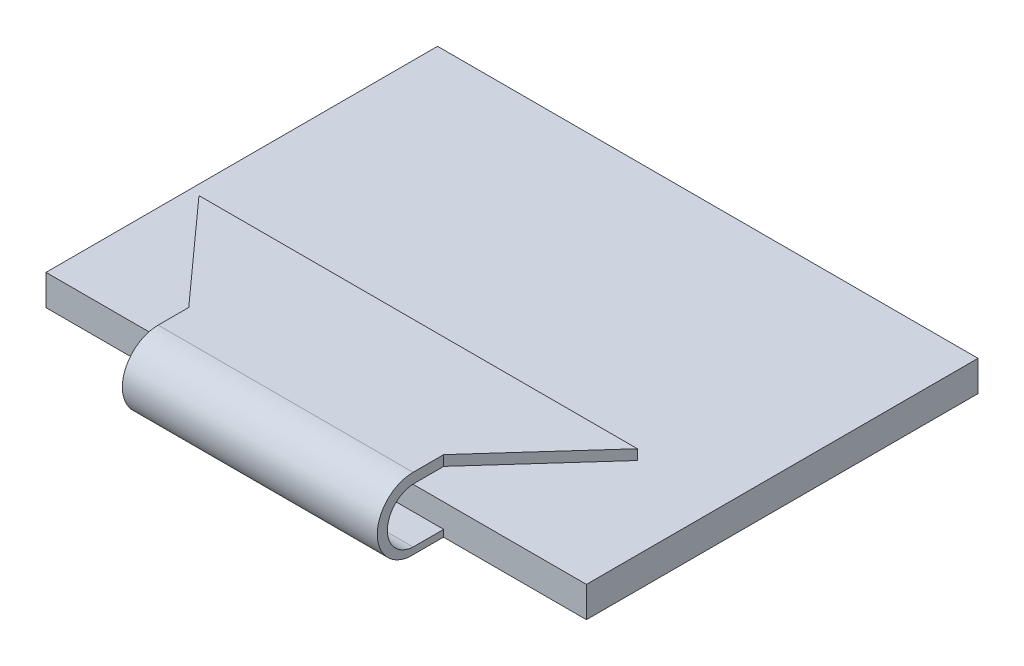
SolidWorks part; units mm, degrees
material "Glass"
ref_plane "Front Plane" through (0, 0, 0) normal (0, 0, 1) x (1, 0, 0)
ref_plane "Top Plane" through (0, 0, 0) normal (0, 1, 0) x (1, 0, 0)
ref_plane "Right Plane" through (0, 0, 0) normal (1, 0, 0) x (0, 0, -1)
sketch "Sketch1" plane through (0, 0, 0) normal (0, 1, 0) x (1, 0, 0)
  line L1 (-9.2826, 6.5217) -> (17.2174, 6.5217)
  line L2 (-9.2826, 6.5217) -> (-9.2826, -12.6783)
  line L3 (-9.2826, -12.6783) -> (17.2174, -12.6783)
  line L4 (17.2174, 6.5217) -> (17.2174, -12.6783)
  dimension "D1" = 19.2
  dimension "D2" = 26.5
extrude "Boss-Extrude1" add sketch "Sketch1" along normal blind 1.5
sketch "Sketch2" plane through (0, 0, 12.6783) normal (0, 0, 1) x (1, 0, 0)
  line L0 (-9.2826, 1.5) -> (-9.2826, 0) construction
  line L1 (-2.2826, 0.01) -> (10.2174, 0.01)
  line L2 (-2.2826, 0.01) -> (-2.2826, 3.51)
  line L3 (-2.2826, 3.51) -> (10.2174, 3.51)
  line L4 (10.2174, 0.01) -> (10.2174, 3.51)
  line L5 (-9.2826, 0) -> (17.2174, 0) construction
  dimension "D1" = 12.5
  dimension "D2" = 7
  dimension "D3" = 0.01
  dimension "D4" = 3.5
extrude "Boss-Extrude2" add sketch "Sketch2" along normal blind 3.5 contours L3 L4 L1 L2
sketch "Sketch3" plane through (-2.2826, 0, 0) normal (-1, 0, 0) x (0, 0, 1)
  line L0 (16.1783, 3.51) -> (12.6783, 3.51) construction
  line L1 (16.1783, 0.01) -> (16.1783, 3.51) construction
  line L2 (12.6783, 3.01) -> (12.6783, 0.3368)
  line L3 (14.1782, -0.0031) -> (12.6783, 0.01)
  line L4 (12.6783, 0.01) -> (12.6783, 1.5) construction
  line L5 (16.1783, 0.01) -> (12.6783, 0.01) construction
  line L6 (12.6783, 0.3368) -> (14.1783, 0.3368)
  line L7 (12.6783, 0.01) -> (12.6783, 0.3368)
  line L8 (14.1783, 3.51) -> (12.6783, 3.51)
  line L9 (12.6783, 1.5) -> (12.6783, 3.51) construction
  line L10 (12.6783, 3.51) -> (12.6783, 3.01)
  line L11 (12.6783, 3.01) -> (14.1783, 3.01)
  line L12 (14.1783, 3.51) -> (16.1783, 3.51)
  line L13 (16.1783, 3.51) -> (16.1783, 0.01)
  line L14 (16.1783, 0.01) -> (14.1782, -0.0031)
  arc A0 (14.1783, 3.51) -> (14.1782, -0.0031) centre (14.1782, 1.7535) cw
  arc A3 (14.1783, 3.01) -> (14.1783, 0.3368) centre (14.1007, 1.6734) cw
  point P0 (14.1783, 3.51)
  point P22 (15.9348, 1.7534)
  point P23 (15.5149, 1.6734)
  line M2 (12.6783, 1.5) -> (12.6783, 0.01)
  line M3 (12.6783, 0.01) -> (16.1783, 0.01)
  line M4 (16.1783, 0.01) -> (16.1783, 3.51)
  line M5 (16.1783, 3.51) -> (12.6783, 3.51)
  line M6 (12.6783, 3.51) -> (12.6783, 1.5)
  dimension "D1" = 2
  dimension "D2" = 0.5
  dimension "D3" = 0.5
extrude "Cut-Extrude1" cut sketch "Sketch3" against normal blind 18 contours A3 L11 L6 M6 M2 | A0 M5 M3 M4
sketch "Sketch4" plane through (0, 0, 12.6783) normal (0, 0, -1) x (-1, 0, 0)
  line L1 (-10.2174, 3.51) -> (2.2826, 3.51)
  line L2 (-10.2174, 3.51) -> (-10.2174, 3.01)
  line L3 (-10.2174, 3.01) -> (2.2826, 3.01)
  line L4 (2.2826, 3.51) -> (2.2826, 3.01)
extrude "Boss-Extrude3" add sketch "Sketch4" along normal blind 5
sketch "Sketch6" plane through (0, 3.51, 0) normal (0, 1, 0) x (1, 0, 0)
  line L0 (-2.2826, -7.6783) -> (-6.7826, -7.6783)
  line L3 (-2.2826, -14.1783) -> (-2.2826, -7.6783) construction
  line L4 (10.2174, -7.6783) -> (14.7174, -7.6783)
  line L5 (14.7174, -7.6783) -> (10.2174, -12.6783)
  line L6 (-6.7826, -7.6783) -> (-2.2826, -12.6783)
  line L7 (-2.2826, -7.6783) -> (-2.2826, -12.6783)
  line L8 (10.2174, -7.6783) -> (10.2174, -12.6783)
  dimension "D1" = 4.5
  dimension "D2" = 4.5
extrude "Boss-Extrude4" add sketch "Sketch6" against normal blind 0.5
